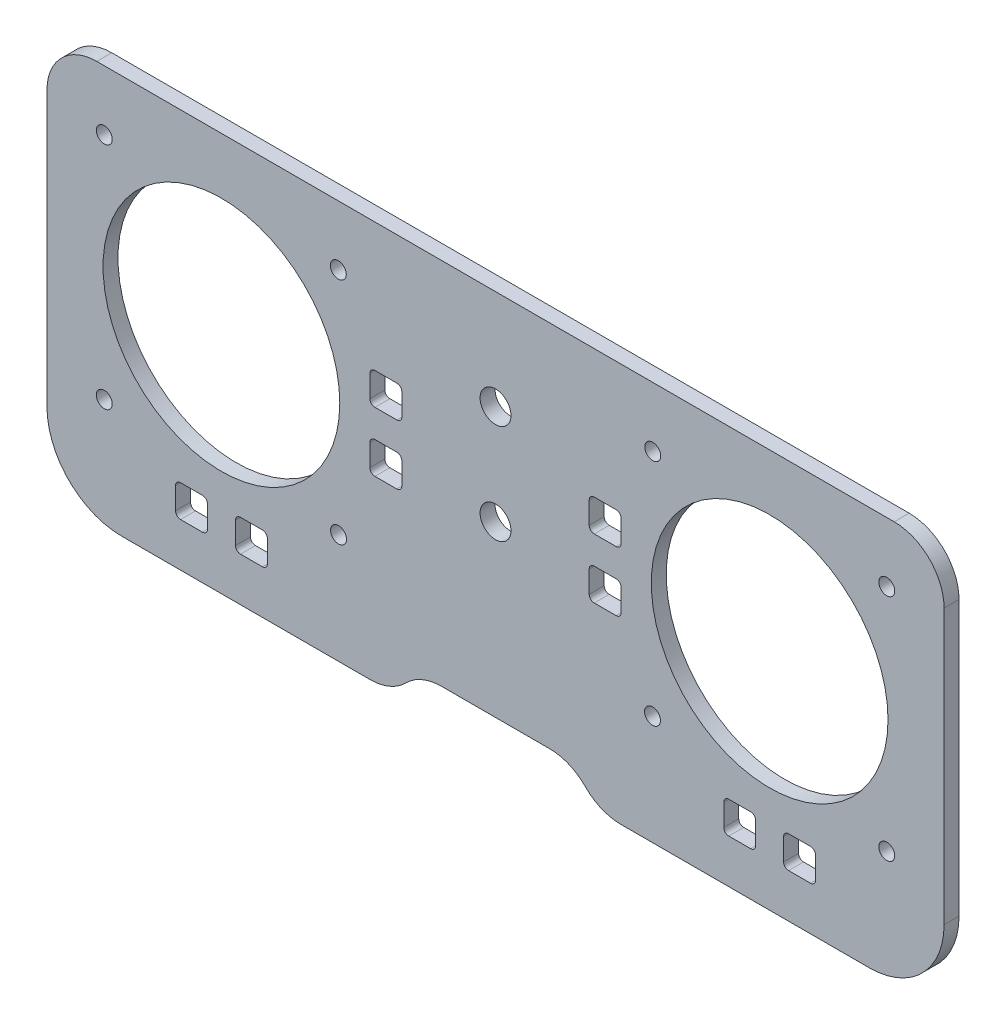
SolidWorks part; units mm, degrees
material "Acrylic (Medium-high impact)"
ref_plane "Front Plane" through (0, 0, 0) normal (0, 0, 1) x (1, 0, 0)
ref_plane "Top Plane" through (0, 0, 0) normal (0, 1, 0) x (1, 0, 0)
ref_plane "Right Plane" through (0, 0, 0) normal (1, 0, 0) x (0, 0, -1)
sketch "Sketch1" plane through (0, 0, 0) normal (0, 0, 1) x (1, 0, 0)
  line L0 (0, 40) -> (0, -40) construction
  line L1 (-90, 40) -> (90, 40)
  line L2 (-90, 40) -> (-90, -40)
  line L3 (-90, -40) -> (90, -40)
  line L4 (90, 40) -> (90, -40)
  line L5 (90, 0) -> (-90, 0) construction
  line L6 (90, 5) -> (-90, 5) construction
  line L7 (-90, 5) -> (-55, 5) construction
  line L8 (90, 5) -> (55, 5) construction
  circle A0 centre (55, 5) radius 23.75
  circle A1 centre (-55, 5) radius 23.75
  point P8 (0, 0)
extrude "Boss-Extrude1" add sketch "Sketch1" along normal blind 3
sketch "Sketch2" plane through (0, 0, 3) normal (0, 0, 1) x (1, 0, 0)
  line L0 (-55, 5) -> (-55, -49995) construction
  line L1 (-55, 5) -> (49945, 5) construction
  line L2 (55, 5) -> (55, -49995) construction
  line L3 (-25, 5) -> (-25, -49995) construction
  line L4 (25, 5) -> (25, -49995) construction
  line L5 (-55, -25) -> (49945, -25) construction
  line L6 (-55, -31) -> (49945, -31) construction
  line L7 (-19, 5) -> (-19, -49995) construction
  line L8 (19, 5) -> (19, -49995) construction
  line L9 (-55, 2) -> (49945, 2) construction
  line L10 (-55, 8) -> (49945, 8) construction
  line L11 (-55, -4) -> (49945, -4) construction
  line L12 (-55, 14) -> (49945, 14) construction
  line L13 (-58, 5) -> (-58, -49995) construction
  line L14 (52, 5) -> (52, -49995) construction
  line L15 (-52, 5) -> (-52, -49995) construction
  line L16 (58, 5) -> (58, -49995) construction
  line L17 (-64, 5) -> (-64, -49995) construction
  line L18 (46, 5) -> (46, -49995) construction
  line L19 (-46, 5) -> (-46, -49995) construction
  line L20 (64, 5) -> (64, -49995) construction
  line L21 (-64.2, -24.8) -> (-64.2, -31.2)
  line L22 (-25, 14) -> (-19, 14) construction
  line L23 (-25, 14) -> (-25, 8) construction
  line L24 (-25, 8) -> (-19, 8) construction
  line L25 (-19, 14) -> (-19, 8) construction
  line L26 (-25, 2) -> (-19, 2) construction
  line L27 (-25, 2) -> (-25, -4) construction
  line L28 (-25, -4) -> (-19, -4) construction
  line L29 (-19, 2) -> (-19, -4) construction
  line L30 (-64, -25) -> (-58, -25) construction
  line L31 (-64, -25) -> (-64, -31) construction
  line L32 (-64, -31) -> (-58, -31) construction
  line L33 (-58, -25) -> (-58, -31) construction
  line L34 (-51.9776, -25) -> (-45.9751, -25) construction
  line L35 (-51.9776, -25) -> (-51.9776, -31) construction
  line L36 (-51.9776, -31) -> (-45.9751, -31) construction
  line L37 (-45.9751, -25) -> (-45.9751, -31) construction
  line L38 (46, -25) -> (52, -25) construction
  line L39 (46, -25) -> (46, -31) construction
  line L40 (46, -31) -> (52, -31) construction
  line L41 (52, -25) -> (52, -31) construction
  line L42 (58, -25) -> (64, -25) construction
  line L43 (58, -25) -> (58, -31) construction
  line L44 (58, -31) -> (64, -31) construction
  line L45 (64, -25) -> (64, -31) construction
  line L46 (19, 14) -> (25, 14) construction
  line L47 (19, 14) -> (19, 8) construction
  line L48 (19, 8) -> (25, 8) construction
  line L49 (25, 14) -> (25, 8) construction
  line L50 (19, 2) -> (25, 2) construction
  line L51 (19, 2) -> (19, -4) construction
  line L52 (19, -4) -> (25, -4) construction
  line L53 (25, 2) -> (25, -4) construction
  line L54 (-64.2, -31.2) -> (-57.8, -31.2)
  line L55 (-57.8, -24.8) -> (-57.8, -31.2)
  line L56 (-64.2, -24.8) -> (-57.8, -24.8)
  line L57 (-52.1776, -24.8) -> (-45.7751, -24.8)
  line L58 (-45.7751, -24.8) -> (-45.7751, -31.2)
  line L59 (-52.1776, -31.2) -> (-45.7751, -31.2)
  line L60 (-52.1776, -24.8) -> (-52.1776, -31.2)
  line L61 (-25.2, -4.2) -> (-18.8, -4.2)
  line L62 (-18.8, 2.2) -> (-18.8, -4.2)
  line L63 (-25.2, 2.2) -> (-18.8, 2.2)
  line L64 (-25.2, 2.2) -> (-25.2, -4.2)
  line L65 (-25.2, 7.8) -> (-18.8, 7.8)
  line L66 (-18.8, 14.2) -> (-18.8, 7.8)
  line L67 (-25.2, 14.2) -> (-18.8, 14.2)
  line L68 (-25.2, 14.2) -> (-25.2, 7.8)
  line L69 (18.8, 2.2) -> (25.2, 2.2)
  line L70 (25.2, 2.2) -> (25.2, -4.2)
  line L71 (18.8, -4.2) -> (25.2, -4.2)
  line L72 (18.8, 2.2) -> (18.8, -4.2)
  line L73 (18.8, 7.8) -> (25.2, 7.8)
  line L74 (25.2, 14.2) -> (25.2, 7.8)
  line L75 (18.8, 14.2) -> (25.2, 14.2)
  line L76 (18.8, 14.2) -> (18.8, 7.8)
  line L77 (45.8, -31.2) -> (52.2, -31.2)
  line L78 (52.2, -24.8) -> (52.2, -31.2)
  line L79 (45.8, -24.8) -> (52.2, -24.8)
  line L80 (45.8, -24.8) -> (45.8, -31.2)
  line L81 (57.8, -31.2) -> (64.2, -31.2)
  line L82 (64.2, -24.8) -> (64.2, -31.2)
  line L83 (57.8, -24.8) -> (64.2, -24.8)
  line L84 (57.8, -24.8) -> (57.8, -31.2)
extrude "Cut-Extrude1" cut sketch "Sketch2" against normal through all
sketch "Sketch3" plane through (0, 0, 3) normal (0, 0, 1) x (1, 0, 0)
  line L0 (0, 40) -> (0, -40) construction
  line L1 (90, 40) -> (-90, 40) construction
  line L2 (-90, -40) -> (90, -40) construction
  line L3 (0, -40) -> (0, -34) construction
  line L4 (0, -34) -> (15, -34) construction
  line L5 (0, -34) -> (-15, -34) construction
  line L6 (-15, -34) -> (-15, -40) construction
  line L7 (-15, -40) -> (-21, -40) construction
  line L8 (-21, -40) -> (-15, -34) construction
  line L9 (15, -34) -> (15, -40) construction
  line L10 (15, -40) -> (21, -40) construction
  line L11 (21, -40) -> (15, -34) construction
  line L12 (-21, -40) -> (-15, -34)
  line L13 (-15, -34) -> (15, -34)
  line L14 (15, -34) -> (21, -40)
  line L15 (21, -40) -> (-21, -40)
extrude "Cut-Extrude2" cut sketch "Sketch3" against normal blind 3
sketch "Sketch4" plane through (0, 0, 3) normal (0, 0, 1) x (1, 0, 0)
  line L0 (-55, -18) -> (49945, -18) construction
  line L1 (-55, 28) -> (49945, 28) construction
  line L2 (0, 0) -> (0, -50000) construction
  line L3 (-55, -18.75) -> (-55, 49981.25) construction
  line L4 (-31.5, -18.75) -> (-31.5, 49981.25) construction
  line L5 (-78.5, -18.75) -> (-78.5, 49981.25) construction
  line L6 (-55, 5) -> (49945, 5) construction
  circle A0 centre (-78.5, 28) radius 1.6
  circle A1 centre (-31.5459, 28) radius 1.6
  circle A2 centre (-31.5, -18) radius 1.6
  circle A3 centre (-78.5, -18) radius 1.6
  circle A4 centre (31.5, -18) radius 1.6
  circle A5 centre (31.5459, 28) radius 1.6
  circle A6 centre (78.5, 28) radius 1.6
  circle A7 centre (78.5, -18) radius 1.6
extrude "Cut-Extrude3" cut sketch "Sketch4" against normal blind 3
sketch "Sketch7" plane through (0, 0, 3) normal (0, 0, 1) x (1, 0, 0)
  line L0 (0, 0) -> (0, -50000) construction
  line L1 (0, 0) -> (0, 20) construction
  circle A0 centre (0, 0) radius 3.1
  circle A1 centre (0, 20) radius 3.1
  point P7 (0, 0)
  point P8 (0, 0)
  point P9 (0, 0)
  point P10 (0, 0)
extrude "Cut-Extrude4" cut sketch "Sketch7" against normal blind 3
fillet "Fillet1" radius 10 2 edges at (90, 40, 1.5) (-90, 40, 1.5)
fillet "Fillet2" radius 15 2 edges at (90, -40, 1.5) (-90, -40, 1.5)
fillet "Fillet3" radius 10 4 edges at (21, -40, 1.5) (15, -34, 1.5) (-15, -34, 1.5) (-21, -40, 1.5)
fillet "Fillet4" radius 1 32 edges at (-57.8, -31.2, 1.5) (-64.2, -24.8, 1.5) (-57.8, -24.8, 1.5) (-45.7751, -24.8, 1.5) (-45.7751, -31.2, 1.5) (-52.1776, -31.2, 1.5) (-52.1776, -24.8, 1.5) (-18.8, 2.2, 1.5) (-18.8, -4.2, 1.5) (-25.2, -4.2, 1.5) (-25.2, 2.2, 1.5) (-18.8, 14.2, 1.5) (-18.8, 7.8, 1.5) (-25.2, 7.8, 1.5) (-25.2, 14.2, 1.5) (25.2, 2.2, 1.5) (25.2, -4.2, 1.5) (18.8, -4.2, 1.5) (18.8, 2.2, 1.5) (25.2, 14.2, 1.5) (25.2, 7.8, 1.5) (18.8, 7.8, 1.5) (18.8, 14.2, 1.5) (52.2, -24.8, 1.5) (52.2, -31.2, 1.5) (45.8, -31.2, 1.5) (45.8, -24.8, 1.5) (64.2, -24.8, 1.5) (64.2, -31.2, 1.5) (57.8, -31.2, 1.5) (57.8, -24.8, 1.5) (-64.2, -31.2, 1.5)
